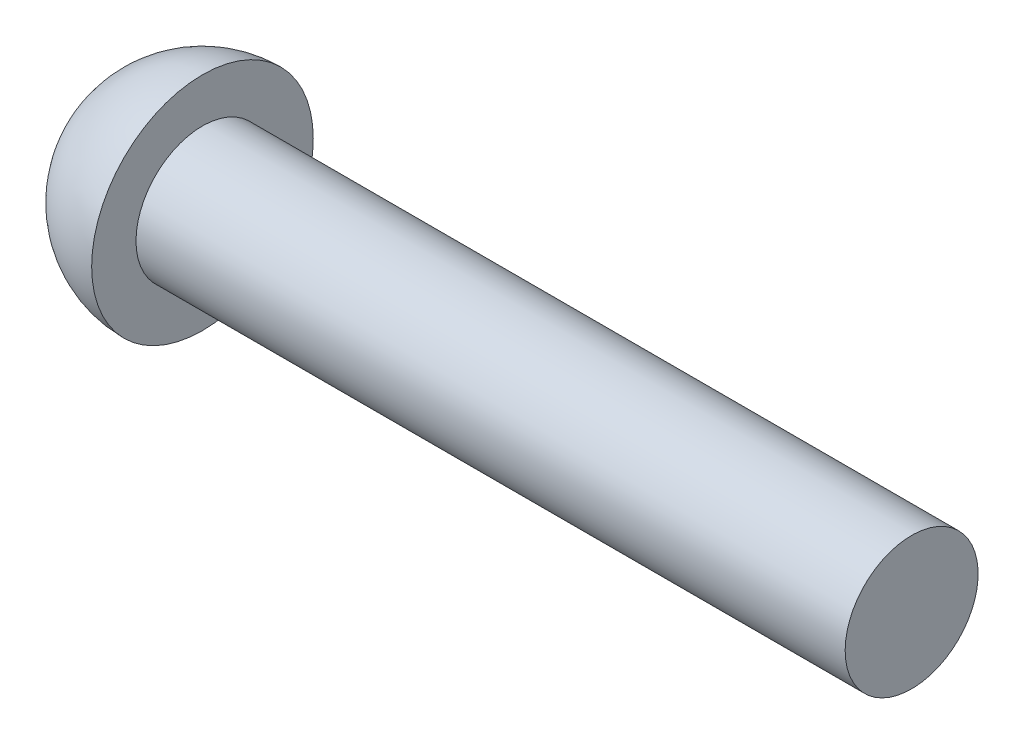
SolidWorks part; units mm, degrees
ref_plane "Front" through (0, 0, 0) normal (0, 0, 1) x (1, 0, 0)
ref_plane "Top" through (0, 0, 0) normal (0, 1, 0) x (1, 0, 0)
ref_plane "Right" through (0, 0, 0) normal (1, 0, 0) x (0, 0, -1)
sketch "Эскиз1" plane through (0, 0, 0) normal (0, 0, 1) x (1, 0, 0)
  line L0 (-11.9014, 0) -> (14.0049, 0) construction
  line L1 (16, 0) -> (-2.5, 0)
  line L2 (0, 1.5) -> (16, 1.5)
  line L3 (16, 1.5) -> (16, 0)
  line L5 (0, 1.5) -> (0, 2.5)
  arc A0 (0, 2.5) -> (-2.5, 0) centre (0, 0) ccw
  dimension "D1" = 18.5
  dimension "D2" = 1.5
  dimension "D3" = 2.5
revolve "Повернуть1" add sketch "Эскиз1" angle 360 about L0
